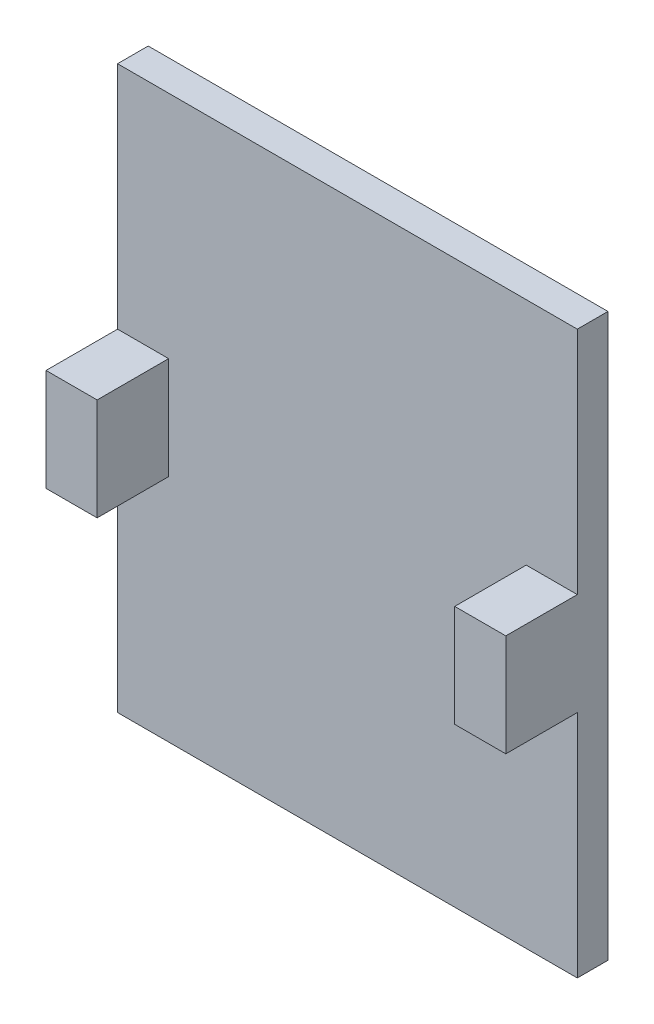
SolidWorks part; units mm, degrees
ref_plane "Front Plane" through (0, 0, 0) normal (0, 0, 1) x (1, 0, 0)
ref_plane "Top Plane" through (0, 0, 0) normal (0, 1, 0) x (1, 0, 0)
ref_plane "Right Plane" through (0, 0, 0) normal (1, 0, 0) x (0, 0, -1)
sketch "Sketch1" plane through (0, 0, 0) normal (0, 0, 1) x (1, 0, 0)
  line L1 (-22500, -27500) -> (22500, -27500)
  line L2 (-22500, -27500) -> (-22500, 27500)
  line L3 (-22500, 27500) -> (22500, 27500)
  line L4 (22500, -27500) -> (22500, 27500)
extrude "Boss-Extrude1" add sketch "Sketch1" along normal blind 3000
sketch "Sketch2" plane through (0, 0, 0) normal (0, 0, 1) x (1, 0, 0)
  circle A0 centre (0, 0) radius 14000
sketch "Sketch3" plane through (0, 0, 0) normal (0, 0, 1) x (1, 0, 0)
  line L0 (-22500, 27500) -> (-22500, -27500) construction
  line L1 (-22500, -5000) -> (-17500, -5000)
  line L2 (-22500, -5000) -> (-22500, 5000)
  line L3 (-22500, 5000) -> (-17500, 5000)
  line L4 (-17500, -5000) -> (-17500, 5000)
  line L5 (22500, -27500) -> (22500, 27500) construction
  line L6 (17500, -5000) -> (22500, -5000)
  line L7 (17500, -5000) -> (17500, 5000)
  line L8 (17500, 5000) -> (22500, 5000)
  line L9 (22500, -5000) -> (22500, 5000)
extrude "Boss-Extrude2" add sketch "Sketch3" along normal blind 10000
sketch "Sketch4" plane through (0, 0, 0) normal (0, 0, 1) x (1, 0, 0)
  circle A0 centre (-14000, -20000) radius 1000
  circle A1 centre (14000, -20000) radius 1000
